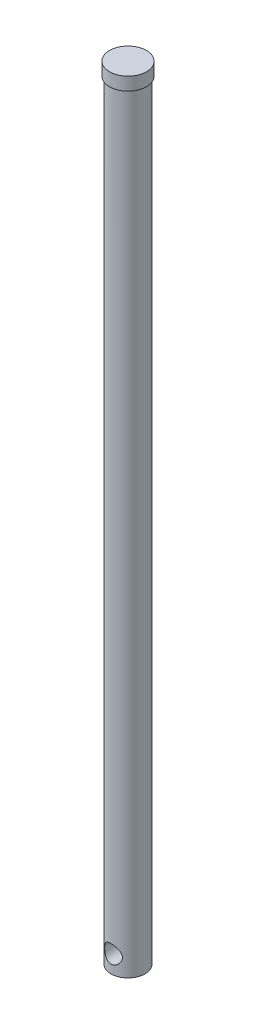
SolidWorks part; units mm, degrees
ref_plane "Front Plane" through (0, 0, 0) normal (0, 0, 1) x (1, 0, 0)
ref_plane "Top Plane" through (0, 0, 0) normal (0, 1, 0) x (1, 0, 0)
ref_plane "Right Plane" through (0, 0, 0) normal (1, 0, 0) x (0, 0, -1)
sketch "Sketch1" plane through (0, 0, 0) normal (0, 1, 0) x (1, 0, 0)
  circle A0 centre (0, 0) radius 4.953
  dimension "D1" = 9.906
extrude "Boss-Extrude1" add sketch "Sketch1" along normal blind 228.6
sketch "Sketch2" plane through (0, 228.6, 0) normal (0, 1, 0) x (1, 0, 0)
  circle A0 centre (0, 0) radius 4.953
  circle A1 centre (0, 0) radius 4.953 construction
  circle A2 centre (0, 0) radius 5.3975
  dimension "D1" = 10.795
extrude "Boss-Extrude2" add sketch "Sketch2" against normal blind 3.81
sketch "Sketch3" plane through (0, 0, 0) normal (0, 0, 1) x (1, 0, 0)
  line L0 (0, 0) -> (0, 5.08) construction
  line L1 (0, -5.9372) -> (0, 5.9372) construction
  dimension "D1" = 5.08
ref_plane "Plane1" through (0, 0, 4.953) normal (0, 0, 1) x (1, 0, 0)
hole_wizard "#6 (0.204) Diameter Hole1" positions "Sketch4" profile "Sketch5" hole size "#6" standard "ANSI Inch" end condition through all
sketch "Sketch4" plane through (0, 0, 4.953) normal (0, 0, 1) x (1, 0, 0)
  point P0 (0, 5.08)
sketch "Sketch5" plane through (0, 5.08, 4.953) normal (1, 0, 0) x (0, -1, 0)
  line L0 (0, 0) -> (0, 10.3505)
  line L1 (0, 10.3505) -> (2.5908, 10.3505)
  line L2 (2.5908, 10.3505) -> (2.5908, 0)
  line L5 (2.5908, 0) -> (0, 0)
  line L11 (0, -6.35) -> (0, 107.95) construction
  dimension "Thru Hole Dia." = 5.1816
  dimension "Thru Hole Depth" = 10.3505
